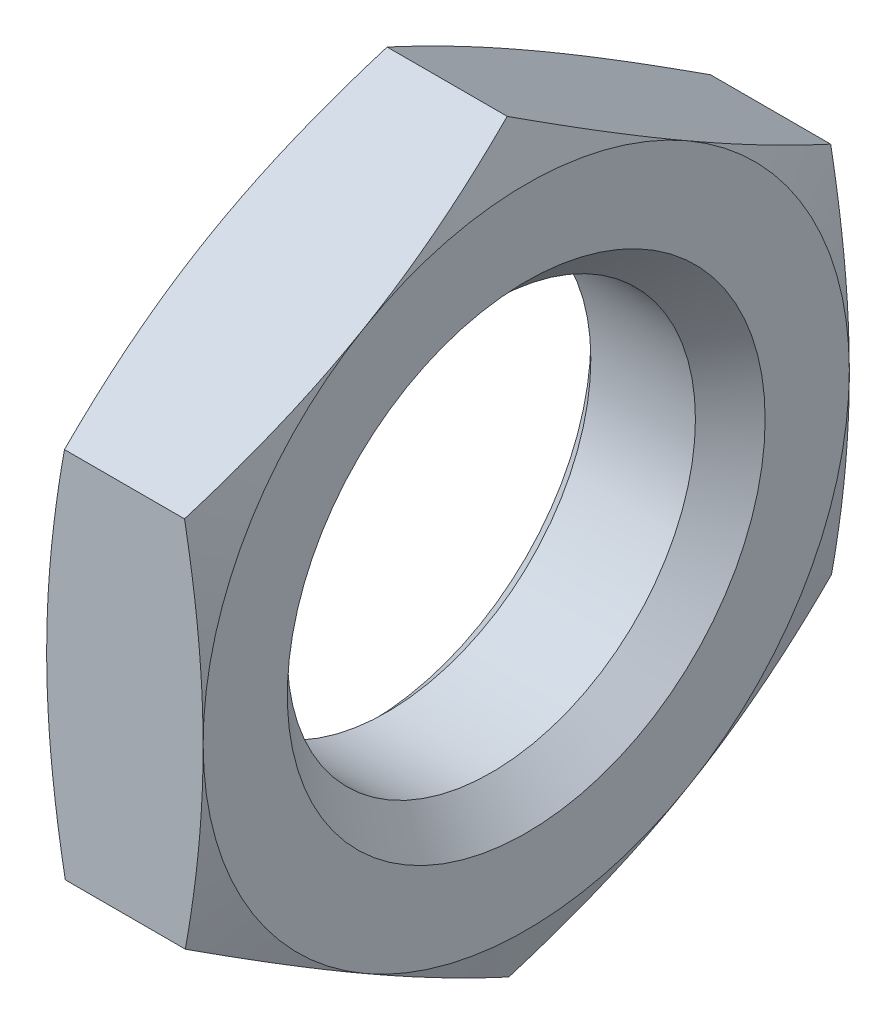
SolidWorks part; units mm, degrees
material "AISI 1020"
ref_plane "Plano superior" through (0, 0, 0) normal (0, 0, 1) x (1, 0, 0)
ref_plane "Plano frontal" through (0, 0, 0) normal (0, 1, 0) x (1, 0, 0)
ref_plane "Plano direito" through (0, 0, 0) normal (1, 0, 0) x (0, 0, -1)
sketch "Esboço1" plane through (0, 0, 0) normal (1, 0, 0) x (0, 0, -1)
  line L1 (9.4879, 5.5058) -> (-0.0242, 10.9696)
  line L2 (-0.0242, 10.9696) -> (-9.5121, 5.4639)
  line L3 (-9.5121, 5.4639) -> (-9.4879, -5.5058)
  line L4 (-9.4879, -5.5058) -> (0.0242, -10.9696)
  line L5 (0.0242, -10.9696) -> (9.5121, -5.4639)
  line L6 (9.5121, -5.4639) -> (9.4879, 5.5058)
  circle A0 centre (0, 0) radius 9.5 construction
  dimension "D1" = 19
extrude "Ressalto-extrusão1" add sketch "Esboço1" along normal blind 4.6
hole_wizard "Furo roscado de M141" positions "Esboço7" profile "Esboço6" tap size "M14" standard "DIN" end condition through all
sketch "Esboço7" plane through (4.6, 0, 0) normal (1, 0, 0) x (0, 0, -1)
  point P0 (0, 0)
  point P3 (0, 0)
sketch "Esboço6" plane through (4.6, 0, 0) normal (0, 1, 0) x (0, 0, -1)
  line L0 (0, 0) -> (0, 4.6)
  line L1 (0, 4.6) -> (6, 4.6)
  line L2 (6, 4.6) -> (6, 1.025)
  line L3 (6, 1.025) -> (7.025, 0)
  line L5 (7.025, 0) -> (0, 0)
  line L6 (-6, 1.025) -> (-7.025, 0) construction
  line L11 (0, -6.35) -> (0, 107.95) construction
  dimension "Thru Tap Drill Dia." = 12
  dimension "Thru Tap Drill Depth" = 4.6
  dimension "Near C'Sink Dia." = 14.05
  dimension "Near C'Sink Angle" = 90
cosmetic thread "Rosca de furo1" parameters "D2"=14
cosmetic thread "Rosca de furo2" parameters "D2"=14
chamfer "Chanfro1" distance 0.5 angle 45 1 edges at (0, 0, -6)
sketch "Esboço8" plane through (0, 0, 0) normal (-1, 0, 0) x (0, 0, 1)
  circle A0 centre (0, 0) radius 9.5
extrude "Corte-extrusão1" cut sketch "Esboço8" against normal blind 13 draft 70 flip side to cut
sketch "Esboço9" plane through (4.6, 0, 0) normal (1, 0, 0) x (0, 0, -1)
  circle A0 centre (0, 0) radius 9.5
extrude "Corte-extrusão2" cut sketch "Esboço9" against normal blind 13 draft 70 flip side to cut
